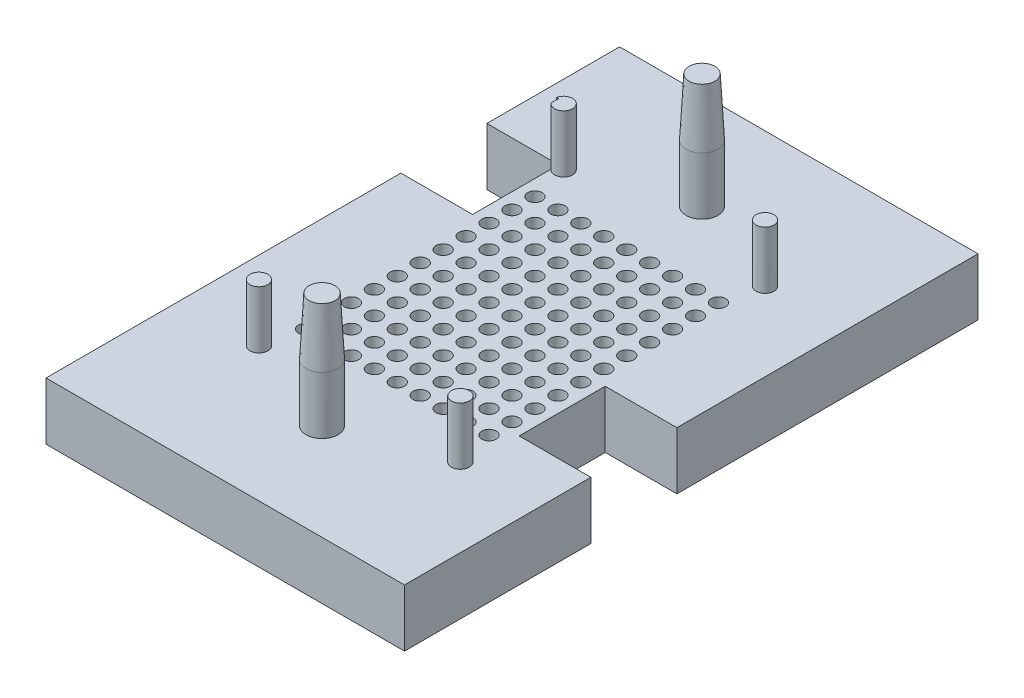
SolidWorks part; units mm, degrees
ref_plane "Front Plane" through (0, 0, 0) normal (0, 0, 1) x (1, 0, 0)
ref_plane "Top Plane" through (0, 0, 0) normal (0, 1, 0) x (1, 0, 0)
ref_plane "Right Plane" through (0, 0, 0) normal (1, 0, 0) x (0, 0, -1)
sketch "Sketch1" plane through (0, 0, 0) normal (0, 1, 0) x (1, 0, 0)
  line L0 (50, 80) -> (0, 0) construction
  line L1 (0, 0) -> (50, 0)
  line L2 (0, 0) -> (0, 80)
  line L3 (0, 80) -> (50, 80)
  line L4 (50, 0) -> (50, 80)
  line L5 (0, 80) -> (50, 0) construction
  circle A0 centre (25, 40) radius 1
  circle A1 centre (28.2, 40) radius 1
  circle A2 centre (31.4, 40) radius 1
  circle A3 centre (34.6, 40) radius 1
  circle A4 centre (37.8, 40) radius 1
  circle A5 centre (28.2, 43.2) radius 1
  circle A6 centre (31.4, 43.2) radius 1
  circle A7 centre (34.6, 43.2) radius 1
  circle A8 centre (37.8, 43.2) radius 1
  circle A9 centre (28.2, 46.4) radius 1
  circle A10 centre (31.4, 46.4) radius 1
  circle A11 centre (34.6, 46.4) radius 1
  circle A12 centre (37.8, 46.4) radius 1
  circle A13 centre (28.2, 49.6) radius 1
  circle A14 centre (31.4, 49.6) radius 1
  circle A15 centre (34.6, 49.6) radius 1
  circle A16 centre (37.8, 49.6) radius 1
  circle A17 centre (28.2, 52.8) radius 1
  circle A18 centre (31.4, 52.8) radius 1
  circle A19 centre (34.6, 52.8) radius 1
  circle A20 centre (37.8, 52.8) radius 1
  circle A21 centre (28.2, 56) radius 1
  circle A22 centre (31.4, 56) radius 1
  circle A23 centre (34.6, 56) radius 1
  circle A24 centre (37.8, 56) radius 1
  circle A25 centre (25, 43.2) radius 1
  circle A26 centre (25, 46.4) radius 1
  circle A27 centre (25, 49.6) radius 1
  circle A28 centre (25, 52.8) radius 1
  circle A29 centre (25, 56) radius 1
  circle A30 centre (21.8, 40) radius 1
  circle A31 centre (21.8, 43.2) radius 1
  circle A32 centre (21.8, 46.4) radius 1
  circle A33 centre (21.8, 49.6) radius 1
  circle A34 centre (21.8, 52.8) radius 1
  circle A35 centre (21.8, 56) radius 1
  circle A36 centre (18.6, 40) radius 1
  circle A37 centre (18.6, 43.2) radius 1
  circle A38 centre (18.6, 46.4) radius 1
  circle A39 centre (18.6, 49.6) radius 1
  circle A40 centre (18.6, 52.8) radius 1
  circle A41 centre (18.6, 56) radius 1
  circle A42 centre (15.4, 40) radius 1
  circle A43 centre (15.4, 43.2) radius 1
  circle A44 centre (15.4, 46.4) radius 1
  circle A45 centre (15.4, 49.6) radius 1
  circle A46 centre (15.4, 52.8) radius 1
  circle A47 centre (15.4, 56) radius 1
  circle A48 centre (12.2, 40) radius 1
  circle A49 centre (12.2, 43.2) radius 1
  circle A50 centre (12.2, 46.4) radius 1
  circle A51 centre (12.2, 49.6) radius 1
  circle A52 centre (12.2, 52.8) radius 1
  circle A53 centre (12.2, 56) radius 1
  circle A54 centre (25, 36.8) radius 1
  circle A55 centre (28.2, 36.8) radius 1
  circle A56 centre (31.4, 36.8) radius 1
  circle A57 centre (34.6, 36.8) radius 1
  circle A58 centre (37.8, 36.8) radius 1
  circle A59 centre (21.8, 36.8) radius 1
  circle A60 centre (18.6, 36.8) radius 1
  circle A61 centre (15.4, 36.8) radius 1
  circle A62 centre (12.2, 36.8) radius 1
  circle A63 centre (25, 33.6) radius 1
  circle A64 centre (28.2, 33.6) radius 1
  circle A65 centre (31.4, 33.6) radius 1
  circle A66 centre (34.6, 33.6) radius 1
  circle A67 centre (37.8, 33.6) radius 1
  circle A68 centre (21.8, 33.6) radius 1
  circle A69 centre (18.6, 33.6) radius 1
  circle A70 centre (15.4, 33.6) radius 1
  circle A71 centre (12.2, 33.6) radius 1
  circle A72 centre (25, 30.4) radius 1
  circle A73 centre (28.2, 30.4) radius 1
  circle A74 centre (31.4, 30.4) radius 1
  circle A75 centre (34.6, 30.4) radius 1
  circle A76 centre (37.8, 30.4) radius 1
  circle A77 centre (21.8, 30.4) radius 1
  circle A78 centre (18.6, 30.4) radius 1
  circle A79 centre (15.4, 30.4) radius 1
  circle A80 centre (12.2, 30.4) radius 1
  circle A81 centre (25, 27.2) radius 1
  circle A82 centre (28.2, 27.2) radius 1
  circle A83 centre (31.4, 27.2) radius 1
  circle A84 centre (34.6, 27.2) radius 1
  circle A85 centre (37.8, 27.2) radius 1
  circle A86 centre (21.8, 27.2) radius 1
  circle A87 centre (18.6, 27.2) radius 1
  circle A88 centre (15.4, 27.2) radius 1
  circle A89 centre (12.2, 27.2) radius 1
  circle A90 centre (25, 24) radius 1
  circle A91 centre (28.2, 24) radius 1
  circle A92 centre (31.4, 24) radius 1
  circle A93 centre (34.6, 24) radius 1
  circle A94 centre (37.8, 24) radius 1
  circle A95 centre (21.8, 24) radius 1
  circle A96 centre (18.6, 24) radius 1
  circle A97 centre (15.4, 24) radius 1
  circle A98 centre (12.2, 24) radius 1
  point P9 (25, 40)
  point P70 (21.8, 40)
  point P83 (18.6, 40)
  point P96 (15.4, 40)
  point P109 (12.2, 40)
  point P123 (25, 36.8)
  point P133 (21.8, 36.8)
  point P136 (18.6, 36.8)
  point P139 (15.4, 36.8)
  point P142 (12.2, 36.8)
  point P146 (25, 33.6)
  point P156 (21.8, 33.6)
  point P159 (18.6, 33.6)
  point P162 (15.4, 33.6)
  point P165 (12.2, 33.6)
  point P169 (25, 30.4)
  point P179 (21.8, 30.4)
  point P182 (18.6, 30.4)
  point P185 (15.4, 30.4)
  point P188 (12.2, 30.4)
  point P192 (25, 27.2)
  point P202 (21.8, 27.2)
  point P205 (18.6, 27.2)
  point P208 (15.4, 27.2)
  point P211 (12.2, 27.2)
  point P215 (25, 24)
  point P225 (21.8, 24)
  point P228 (18.6, 24)
  point P231 (15.4, 24)
  point P234 (12.2, 24)
  dimension "D3" = 2
  dimension "D6" = 3.2
  dimension "D7" = 3.2
  dimension "D11" = 3.2
  dimension "D1" = 50
  dimension "D2" = 80
  dimension "D9" = 3.2
  dimension "D4" = 5
  dimension "D5" = 6
  dimension "D8" = 5
  dimension "D10" = 6
extrude "Boss-Extrude1" add sketch "Sketch1" along normal blind 8
sketch "Sketch2" plane through (0, 8, 0) normal (0, 1, 0) x (1, 0, 0)
  line L0 (0, 40) -> (50, 40) construction
  line L1 (0, 80) -> (0, 0) construction
  line L2 (50, 0) -> (50, 80) construction
  line L3 (10.95, 61.25) -> (25, 61.25) construction
  line L4 (25, 61.25) -> (39.05, 61.25) construction
  line L5 (25, 18.75) -> (39.05, 18.75) construction
  line L6 (10.95, 18.75) -> (25, 18.75) construction
  circle A0 centre (25, 66.5) radius 2.225
  circle A1 centre (10.95, 61.25) radius 1.25
  circle A2 centre (39.05, 61.25) radius 1.25
  circle A3 centre (39.05, 18.75) radius 1.25
  circle A4 centre (10.95, 18.75) radius 1.25
  circle A5 centre (25, 13.5) radius 2.225
  point P6 (25, 40)
  dimension "D1" = 4.45
  dimension "D3" = 2.5
  dimension "D2" = 26.5
  dimension "D4" = 14.05
  dimension "D5" = 21.25
extrude "Boss-Extrude2" add sketch "Sketch2" along normal blind 8
ref_plane "Plane1" through (25, 0, 0) normal (-1, 0, 0) x (0, 0, 1)
sketch "Sketch3" plane through (25, 0, 0) normal (-1, 0, 0) x (0, 0, 1)
  line L0 (-66.5, 16) -> (-66.5, 24)
  line L1 (-64.275, 16) -> (-68.725, 16) construction
  line L2 (-66.5, 24) -> (-68.3, 24)
  line L3 (-68.3, 24) -> (-68.725, 16)
  line L4 (-68.725, 16) -> (-66.5, 16)
  dimension "D1" = 1.8
  dimension "D2" = 8
revolve "Revolve1" add sketch "Sketch3" angle 360 about L0
ref_plane "Plane2" through (0, 0, -40) normal (0, 0, -1) x (-1, 0, 0)
mirror "Mirror1" about plane through (0, 0, -40) normal (0, 0, -1) of "Revolve1"
sketch "Sketch5" plane through (0, 0, 0) normal (0, -1, 0) x (1, 0, 0)
  line L0 (0, -80) -> (0, 0) construction
  line L1 (0, -61.5) -> (10, -61.5)
  line L2 (0, -61.5) -> (0, -49.5)
  line L3 (0, -49.5) -> (10, -49.5)
  line L4 (10, -61.5) -> (10, -49.5)
  line L5 (50, 0) -> (50, -80) construction
  line L6 (50, -26) -> (40, -26)
  line L7 (50, -26) -> (50, -38)
  line L8 (50, -38) -> (40, -38)
  line L9 (40, -26) -> (40, -38)
  line L11 (50, -80) -> (0, -80) construction
  dimension "D1" = 10
  dimension "D2" = 12
  dimension "D3" = 30.5
  dimension "D4" = 54
extrude "Cut-Extrude2" cut sketch "Sketch5" against normal through all
